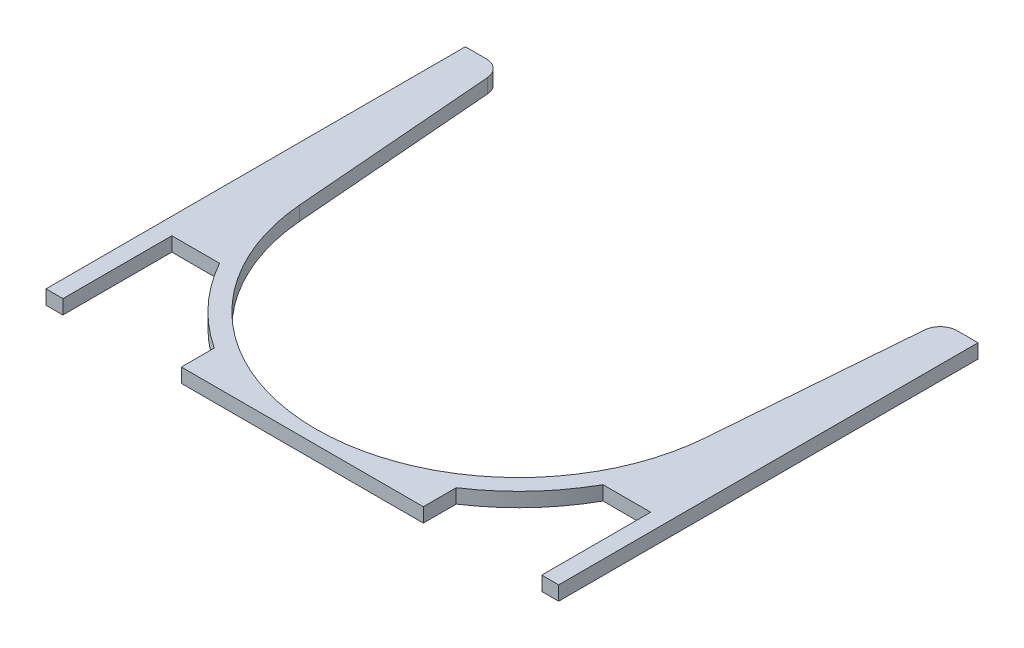
SolidWorks part; units mm, degrees
ref_plane "Front Plane" through (0, 0, 0) normal (0, 0, 1) x (1, 0, 0)
ref_plane "Top Plane" through (0, 0, 0) normal (0, 1, 0) x (1, 0, 0)
ref_plane "Right Plane" through (0, 0, 0) normal (1, 0, 0) x (0, 0, -1)
sketch "Sketch1" plane through (0, 0, 0) normal (0, 1, 0) x (1, 0, 0)
  line L1 (0, 0) -> (192.532, 0)
  line L2 (0, 0) -> (0, 157.48)
  line L3 (0, 157.48) -> (192.532, 157.48)
  line L4 (192.532, 0) -> (192.532, 157.48)
  dimension "D1" = 157.48
  dimension "D2" = 192.532
extrude "Base" add sketch "Sketch1" along normal blind 5.334
sketch "Sketch2" plane through (0, 5.334, 0) normal (0, 1, 0) x (1, 0, 0)
  line L0 (20.331, 74.93) -> (13.716, 157.48)
  line L1 (192.532, 157.48) -> (0, 157.48) construction
  line L2 (172.201, 74.93) -> (178.816, 157.48)
  line L3 (20.331, 74.93) -> (0, 74.93) construction
  line L4 (0, 157.48) -> (0, 0) construction
  line L5 (172.201, 74.93) -> (192.532, 74.93) construction
  line L6 (192.532, 0) -> (192.532, 157.48) construction
  line L7 (13.716, 157.48) -> (0, 157.48) construction
  line L8 (178.816, 157.48) -> (192.532, 157.48) construction
  arc A0 (20.331, 74.93) -> (172.201, 74.93) centre (96.266, 81.28) ccw
  dimension "D1" = 76.2
  dimension "D2" = 76.2
  dimension "D3" = 82.55
  dimension "D4" = 165.1
extrude "Center Cut" cut sketch "Sketch2" against normal through all and the other way through all flip side to cut
fillet "Fillet1" radius 6.35 2 edges at (178.816, 2.667, -157.48) (13.716, 2.667, -157.48)
sketch "Sketch7" plane through (0, 5.334, 0) normal (0, 1, 0) x (1, 0, 0)
  line L0 (0, 157.48) -> (0, 0) construction
  line L1 (0, 0) -> (192.532, 0) construction
  line L2 (96.266, 0) -> (96.266, 50000) construction
  line L3 (6.35, 40.9102) -> (24.2606, 40.9102)
  line L4 (186.182, 40.9102) -> (186.182, 0)
  line L5 (141.704, 12.3606) -> (141.704, 0)
  line L6 (141.704, 0) -> (186.182, 0)
  line L7 (186.182, 40.9102) -> (168.2714, 40.9102)
  line L10 (50.828, 0) -> (6.35, 0)
  line L12 (50.828, 12.3606) -> (50.828, 0)
  line L15 (6.35, 40.9102) -> (6.35, 0)
  arc A0 (168.2714, 40.9102) -> (141.704, 12.3606) centre (96.266, 81.28) cw
  arc A3 (14.0031, 74.4008) -> (178.5289, 74.4008) centre (96.266, 81.28) ccw
  arc A4 (24.2606, 40.9102) -> (50.828, 12.3606) centre (96.266, 81.28) ccw
  point P8 (96.266, 0)
  dimension "D1" = 6.35
  dimension "D2" = 44.478
  dimension "D3" = 17.9106
  dimension "D5" = 6.35
extrude "Cut-Extrude3" cut sketch "Sketch7" against normal through all
equation "\"material\"= \"gmaterial@full.assembly\""
equation "\"D2@Sketch1\"=8-(2*\"material\")"
equation "\"D1@Base\"=\"material\""
